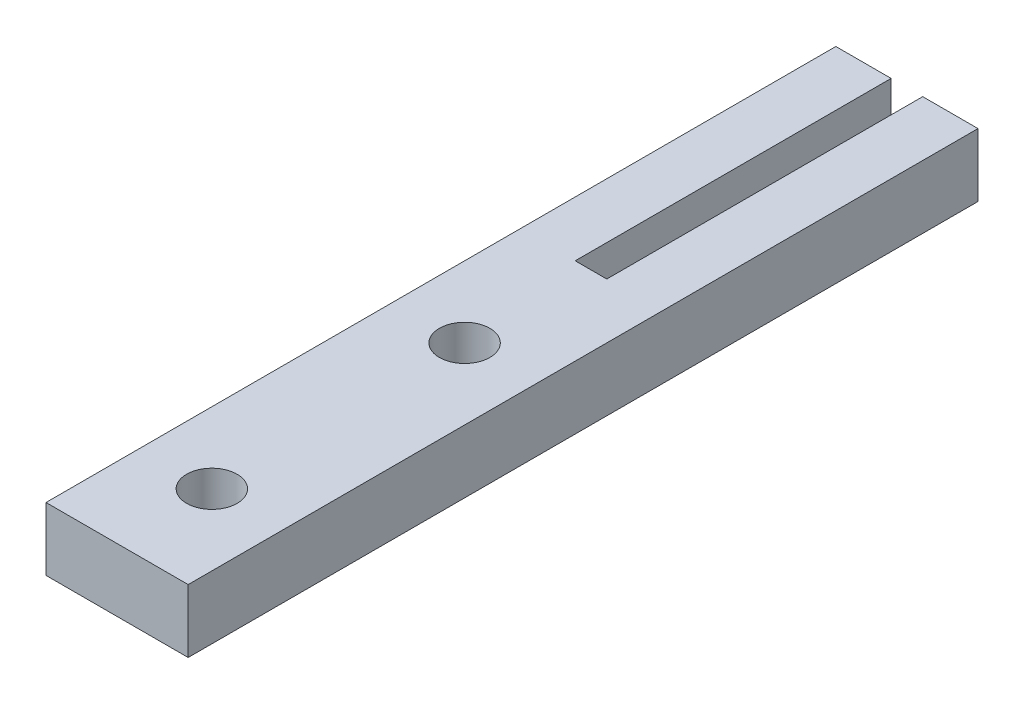
SolidWorks part; units mm, degrees
ref_plane "Front" through (0, 0, 0) normal (0, 0, 1) x (1, 0, 0)
ref_plane "Top" through (0, 0, 0) normal (0, 1, 0) x (1, 0, 0)
ref_plane "Right" through (0, 0, 0) normal (1, 0, 0) x (0, 0, -1)
sketch "Sketch1" plane through (0, 0, 0) normal (0, 1, 0) x (1, 0, 0)
  line L0 (0, 0) -> (0, -16)
  line L1 (0, -16) -> (0, -22)
  line L2 (0, -22) -> (-4.5, -22)
  line L3 (-4.5, -22) -> (-4.5, 28)
  line L4 (-4.5, 28) -> (4.5, 28)
  line L5 (4.5, 28) -> (4.5, -22)
  line L6 (4.5, -22) -> (0, -22)
  circle A0 centre (0, -16) radius 1.6
  circle A1 centre (0, 0) radius 1.6
  dimension "D2" = 4.5
  dimension "D1" = 16
  dimension "D3" = 4.5
  dimension "D4" = 6
  dimension "D5" = 50
extrude "Boss-Extrude1" add sketch "Sketch1" along normal blind 4
sketch "Sketch2" plane through (0, 4, 0) normal (0, 1, 0) x (1, 0, 0)
  line L0 (-1, 28) -> (-1, 8)
  line L1 (-4.5, 28) -> (4.5, 28) construction
  line L2 (-1, 8) -> (1, 8)
  line L3 (1, 8) -> (1, 28)
  line L4 (-4.5, -22) -> (-4.5, 28) construction
  line L5 (4.5, 28) -> (4.5, -22) construction
  dimension "D1" = 20
  dimension "D2" = 3.5
  dimension "D3" = 3.5
extrude "Cut-Extrude1" cut sketch "Sketch2" against normal blind 2 and the other way through all
